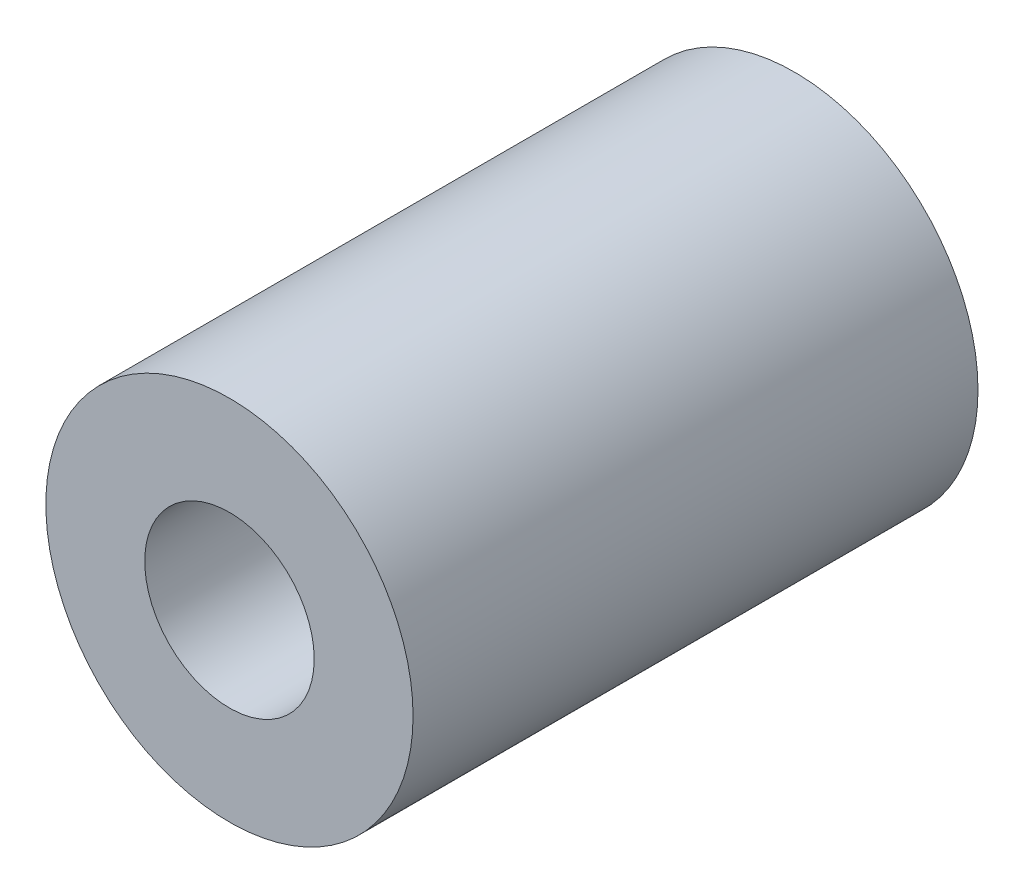
SolidWorks part; units mm, degrees
ref_plane "Front Plane" through (0, 0, 0) normal (0, 0, 1) x (1, 0, 0)
ref_plane "Top Plane" through (0, 0, 0) normal (0, 1, 0) x (1, 0, 0)
ref_plane "Right Plane" through (0, 0, 0) normal (1, 0, 0) x (0, 0, -1)
sketch "Sketch1" plane through (0, 0, 0) normal (0, 0, 1) x (1, 0, 0)
  circle A0 centre (0, 0) radius 3
  circle A1 centre (0, 0) radius 6.5
  dimension "D1" = 6
extrude "Boss-Extrude3" add sketch "Sketch1" along normal blind 20
